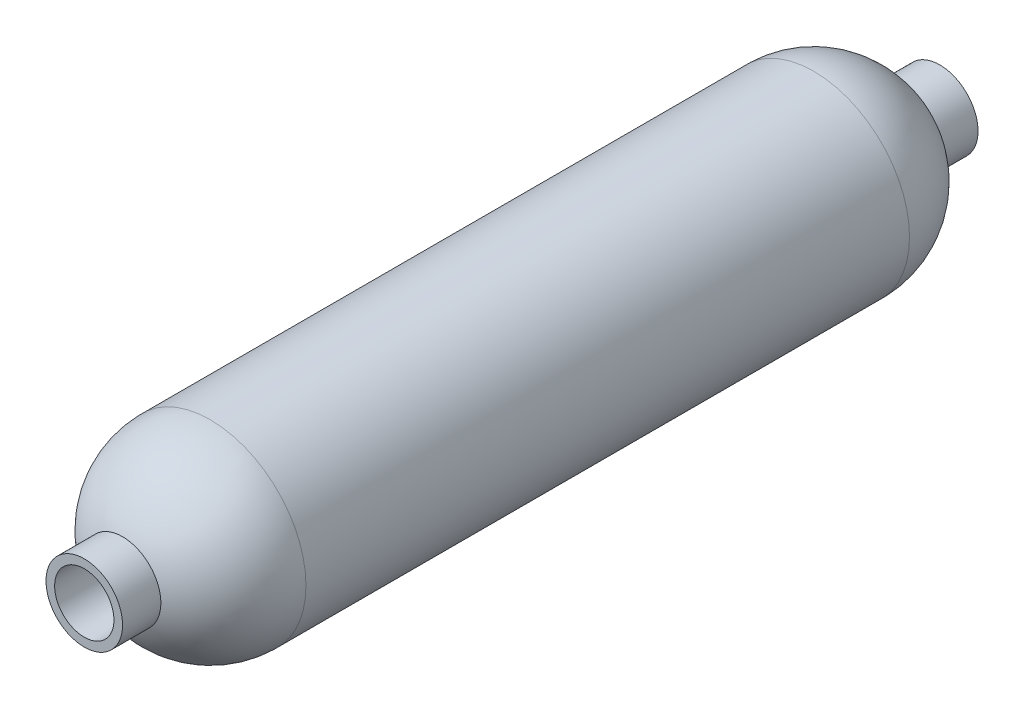
SolidWorks part; units mm, degrees
material "Stainless Steel (ferritic)"
ref_plane "Front Plane" through (0, 0, 0) normal (0, 0, 1) x (1, 0, 0)
ref_plane "Top Plane" through (0, 0, 0) normal (0, 1, 0) x (1, 0, 0)
ref_plane "Right Plane" through (0, 0, 0) normal (1, 0, 0) x (0, 0, -1)
sketch "Sketch1" plane through (0, 0, 0) normal (1, 0, 0) x (0, 0, -1)
  line L0 (113.538, 0) -> (-113.538, 0)
  line L1 (-113.538, 0) -> (-113.538, 10.16)
  line L2 (-113.538, 10.16) -> (-103.378, 10.16)
  line L3 (0, 0) -> (0, 25.4) construction
  line L4 (80.0985, 25.4) -> (-80.0985, 25.4)
  line L5 (-105.4985, 0) -> (-105.4985, 4.0826) construction
  line L6 (105.4985, 0) -> (105.4985, 4.0826) construction
  line L7 (113.538, 10.16) -> (103.378, 10.16)
  line L8 (113.538, 0) -> (113.538, 10.16)
  arc A0 (-80.0985, 25.4) -> (-105.4985, 0) centre (-80.0985, 0) ccw construction
  arc A1 (-80.0985, 25.4) -> (-103.378, 10.16) centre (-80.0985, 0) ccw
  arc A2 (80.0985, 25.4) -> (105.4985, 0) centre (80.0985, 0) cw construction
  arc A3 (80.0985, 25.4) -> (103.378, 10.16) centre (80.0985, 0) cw
  dimension "D1" = 10.16
  dimension "D2" = 227.076
  dimension "D3" = 10.16
  dimension "D4" = 25.4
revolve "Revolve1" add sketch "Sketch1" angle 360 about L0
shell "Shell1" thickness 2.286
